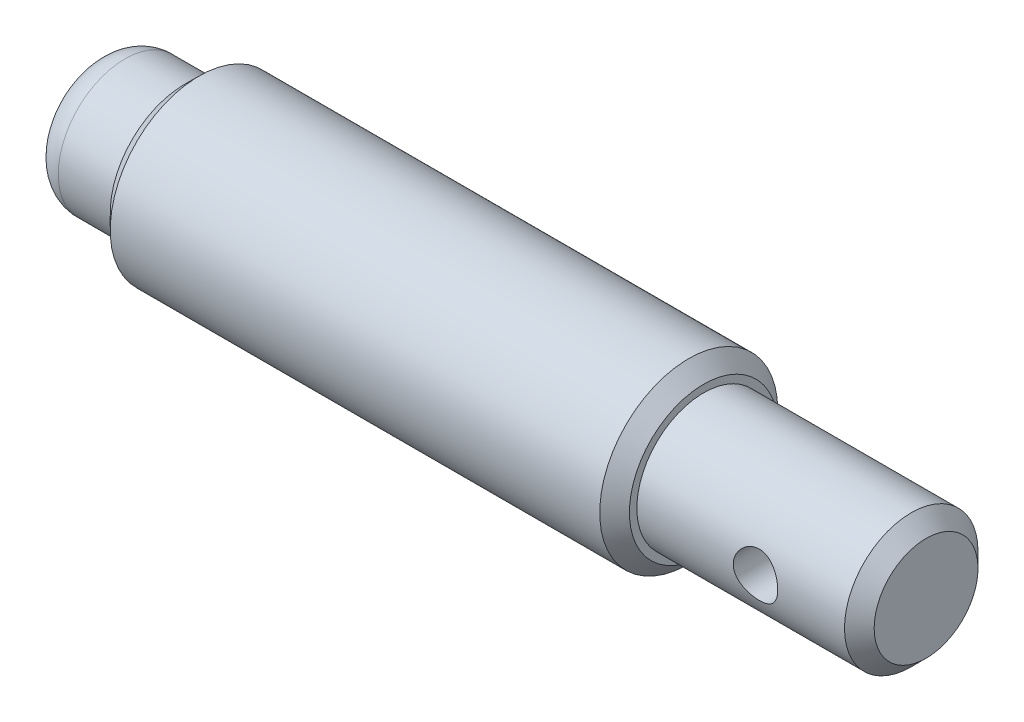
SolidWorks part; units mm, degrees
material "Plain Carbon Steel"
ref_plane "Front Plane" through (0, 0, 0) normal (0, 0, 1) x (1, 0, 0)
ref_plane "Top Plane" through (0, 0, 0) normal (0, 1, 0) x (1, 0, 0)
ref_plane "Right Plane" through (0, 0, 0) normal (1, 0, 0) x (0, 0, -1)
sketch "Sketch1" plane through (0, 0, 0) normal (0, 0, 1) x (1, 0, 0)
  line L0 (0, 0) -> (0, 4.5)
  line L1 (0, 4.5) -> (6, 4.5)
  line L2 (6, 4.5) -> (6, 6)
  line L3 (6, 6) -> (41, 6)
  line L4 (41, 6) -> (41, 4.5)
  line L5 (41, 4.5) -> (56, 4.5)
  line L6 (56, 4.5) -> (56, 0)
  line L7 (56, 0) -> (0, 0)
  line L8 (0, 0) -> (-6.9302, 0) construction
  point P4 (0, 2.25)
  point P11 (56, 2.25)
  dimension "D1" = 6
  dimension "D2" = 35
  dimension "D3" = 56
  dimension "D4" = 9
  dimension "D5" = 12
  dimension "D6" = 9
revolve "Revolve1" add sketch "Sketch1" angle 360 about L8
cosmetic thread "Cosmetic Thread1" parameters "D2"=6.619
chamfer "Chamfer2" distance 1 angle 45 3 edges at (56, 0, -4.5) (41, 0, -6) (6, 0, -6)
fillet "Fillet1" radius 2 1 edges at (0, 0, -4.5)
hole_wizard "Ø3.0 (3) Diameter Hole1" positions "3DSketch1" profile "Sketch2" hole size "Ø3.0" standard "ISO" end condition through all
sketch3d "3DSketch1"
  point P0 (49, 0, 4.5)
  point P4 (49, 0, 4.5)
  dimension "D1" = 8
sketch "Sketch2" plane through (49, 0, 4.5) normal (1, 0, 0) x (0, -1, 0)
  line L0 (0, 0) -> (0, 10.5)
  line L1 (0, 10.5) -> (1.5, 10.5)
  line L2 (1.5, 10.5) -> (1.5, 0)
  line L5 (1.5, 0) -> (0, 0)
  line L11 (0, -6.35) -> (0, 107.95) construction
  dimension "Thru Hole Dia." = 3
  dimension "Thru Hole Depth" = 10.5
